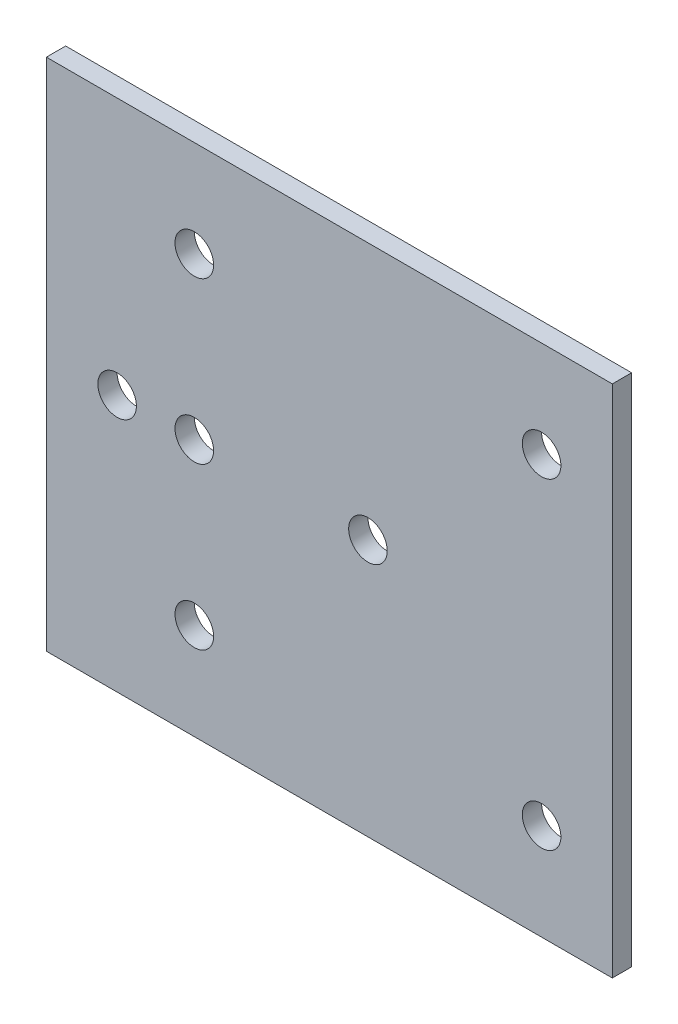
SolidWorks part; units mm, degrees
ref_plane "前视基准面" through (0, 0, 0) normal (0, 0, 1) x (1, 0, 0)
ref_plane "上视基准面" through (0, 0, 0) normal (0, 1, 0) x (1, 0, 0)
ref_plane "右视基准面" through (0, 0, 0) normal (1, 0, 0) x (0, 0, -1)
other "Configuration Table"
sketch "草图1" plane through (0, 0, 0) normal (0, 0, 1) x (1, 0, 0)
  line L0 (38, 40) -> (38, -40)
  line L1 (-50, -40) -> (38, -40)
  line L2 (-50, -40) -> (-50, 40)
  line L3 (-50, 40) -> (38, 40)
  line L5 (0, 40) -> (0, -40) construction
  line L6 (-50, 0) -> (50, 0) construction
  circle A0 centre (-27, 25) radius 3
  circle A1 centre (27, 25) radius 3
  circle A2 centre (27, -25) radius 3
  circle A3 centre (-27, -25) radius 3
  circle A5 centre (0, 0) radius 3
  circle A8 centre (-39, 0) radius 3
  circle A9 centre (-27, 0) radius 3
  point P0 (0, 0)
  point P12 (38.2575, -40)
  dimension "D1" = 6
  dimension "D6" = 6
  dimension "D7" = 11
  dimension "D8" = 6
  dimension "D2" = 54
  dimension "D3" = 50
  dimension "D4" = 50
  dimension "D5" = 15
  dimension "D9" = 12
  dimension "D10" = 11
extrude "凸台-拉伸1" add sketch "草图1" along normal blind 3
